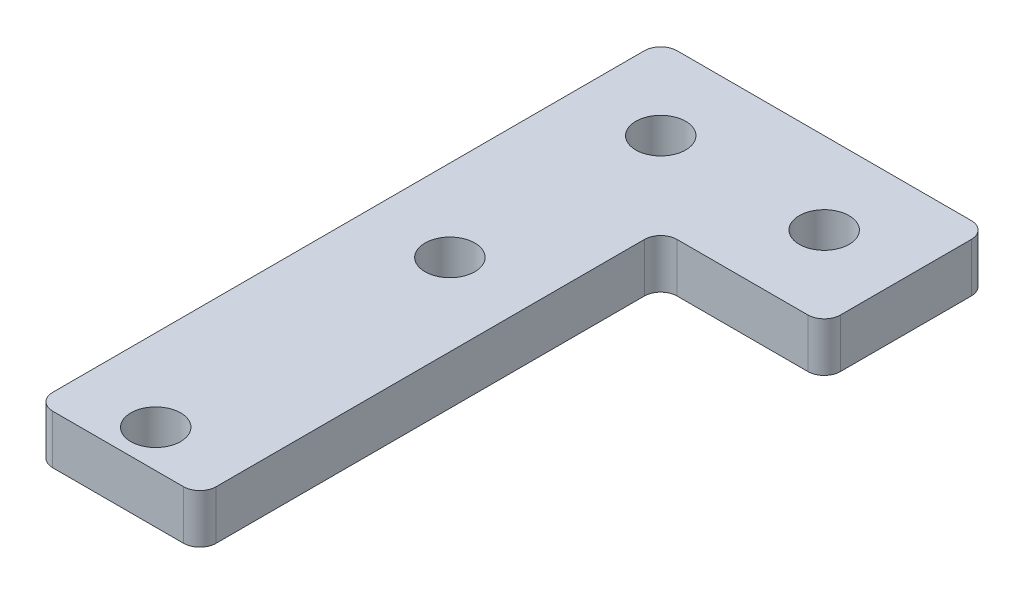
SolidWorks part; units mm, degrees
ref_plane "Front Plane" through (0, 0, 0) normal (0, 0, 1) x (1, 0, 0)
ref_plane "Top Plane" through (0, 0, 0) normal (0, 1, 0) x (1, 0, 0)
ref_plane "Right Plane" through (0, 0, 0) normal (1, 0, 0) x (0, 0, -1)
sketch "Sketch1" plane through (0, 0, 0) normal (0, 1, 0) x (1, 0, 0)
  line L0 (10, 5.6) -> (20, 5.6)
  line L2 (0, 0) -> (0, 15.6)
  line L3 (0, 15.6) -> (20, 15.6)
  line L4 (20, 5.6) -> (20, 15.6)
  line L6 (0, 0) -> (0, -22.6)
  line L7 (0, -22.6) -> (10, -22.6)
  line L8 (10, 5.6) -> (10, -22.6)
  line L9 (5, -22.6) -> (5, 15.6) construction
  line L10 (10, 15.6) -> (10, 5.6) construction
  line L11 (20, 10.6) -> (10, 10.6) construction
  line L12 (10, 10.6) -> (0, 10.6) construction
  circle A4 centre (5, 10.6) radius 1.525
  circle A5 centre (15, 10.6) radius 1.525
  circle A8 centre (5, -2.3) radius 1.525
  circle A9 centre (5, -20.3) radius 1.525
  dimension "D3" = 28.2
  dimension "D4" = 10
  dimension "D5" = 3.05
  dimension "D7" = 2.3
  dimension "D8" = 3.05
  dimension "D1" = 20
  dimension "D2" = 10
  dimension "D6" = 2.3
  dimension "D15" = 22.6
extrude "Boss-Extrude1" add sketch "Sketch1" along normal blind 3
fillet "Fillet1" radius 1 6 edges at (0, 1.5, -15.6) (20, 1.5, -15.6) (10, 1.5, -5.6) (20, 1.5, -5.6) (0, 1.5, 22.6) (10, 1.5, 22.6)
